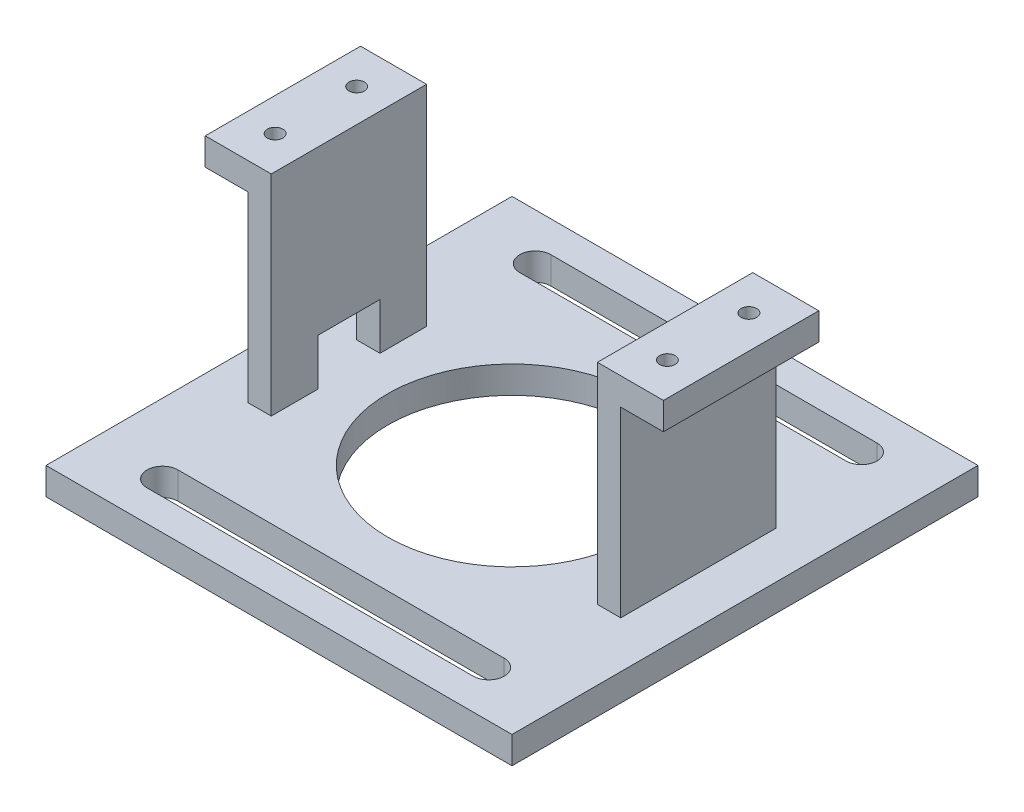
SolidWorks part; units mm, degrees
ref_plane "Alzado" through (0, 0, 0) normal (0, 0, 1) x (1, 0, 0)
ref_plane "Planta" through (0, 0, 0) normal (0, 1, 0) x (1, 0, 0)
ref_plane "Vista lateral" through (0, 0, 0) normal (1, 0, 0) x (0, 0, -1)
sketch "Croquis1" plane through (0, 0, 0) normal (0, 1, 0) x (1, 0, 0)
  line L0 (-49.5899, 38.6898) -> (-49.5899, -21.3102)
  line L1 (-49.5899, 38.6898) -> (10.4101, 38.6898)
  line L2 (10.4101, 38.6898) -> (10.4101, -21.3102)
  line L3 (10.4101, -21.3102) -> (-49.5899, -21.3102)
extrude "Saliente-Extruir1" add sketch "Croquis1" along normal blind 3.5 contours L3 L0 L1 L2
sketch "Croquis2" plane through (0, 3.5, 0) normal (0, 1, 0) x (1, 0, 0)
  line L9 (1.4101, -1.3102) -> (4.4101, -1.3102)
  line L10 (4.4101, -1.3102) -> (4.4101, 18.6898)
  line L11 (4.4101, 18.6898) -> (1.4101, 18.6898)
  line L12 (1.4101, 18.6898) -> (1.4101, -1.3102)
  line L13 (-40.5899, -1.3102) -> (-43.5899, -1.3102)
  line L14 (-43.5899, -1.3102) -> (-43.5899, 18.6898)
  line L15 (-43.5899, 18.6898) -> (-40.5899, 18.6898)
  line L16 (-40.5899, 18.6898) -> (-40.5899, -1.3102)
extrude "Saliente-Extruir4" add sketch "Croquis2" along normal blind 27
sketch "Croquis7" plane through (0, 3.5, 0) normal (0, 1, 0) x (1, 0, 0)
  circle A0 centre (-19.5899, 8.6898) radius 16
extrude "Cortar-Extruir2" cut sketch "Croquis7" against normal blind 5 contours A0
sketch "Croquis8" plane through (0, 3.5, 0) normal (0, 1, 0) x (1, 0, 0)
  line L2 (1.4101, -17.3102) -> (-40.5899, -17.3102)
  line L4 (-40.5899, -13.3102) -> (1.4101, -13.3102)
  line L6 (1.4101, 30.6898) -> (-40.5899, 30.6898)
  line L8 (1.4101, 34.6898) -> (-40.5899, 34.6898)
  arc A1 (-40.5899, 34.6898) -> (-40.5899, 30.6898) centre (-40.5899, 32.6898) ccw
  arc A2 (-40.5899, -13.3102) -> (-40.5899, -17.3102) centre (-40.5899, -15.3102) ccw
  arc A3 (1.4101, -17.3102) -> (1.4101, -13.3102) centre (1.4101, -15.3102) ccw
  arc A4 (1.4101, 30.6898) -> (1.4101, 34.6898) centre (1.4101, 32.6898) ccw
extrude "Cortar-Extruir3" cut sketch "Croquis8" against normal blind 5
sketch "Croquis9" plane through (4.4101, 0, 0) normal (1, 0, 0) x (0, 0, -1)
  line L0 (-1.3102, 30.5) -> (18.6898, 30.5)
  line L1 (18.6898, 30.5) -> (18.6898, 27)
  line L2 (18.6898, 30.5) -> (18.6898, 3.5) construction
  line L3 (18.6898, 27) -> (-1.3102, 27)
  line L4 (-1.3102, 30.5) -> (-1.3102, 3.5) construction
  line L5 (-1.3102, 27) -> (-1.3102, 30.5)
extrude "Saliente-Extruir5" add sketch "Croquis9" along normal blind 5.5
sketch "Croquis10" plane through (-43.5899, 0, 0) normal (-1, 0, 0) x (0, 0, 1)
  line L0 (1.3102, 30.5) -> (-18.6898, 30.5)
  line L1 (-18.6898, 30.5) -> (-18.6898, 3.5) construction
  line L2 (-18.6898, 30.5) -> (1.3102, 30.5) construction
  line L3 (-18.6898, 30.5) -> (-18.6898, 27)
  line L4 (-18.6898, 27) -> (1.3102, 27)
  line L5 (1.3102, 30.5) -> (1.3102, 3.5) construction
  line L6 (1.3102, 27) -> (1.3102, 30.5)
extrude "Saliente-Extruir6" add sketch "Croquis10" along normal blind 5.5 contours L4 L6 L0 L3
sketch "Croquis11" plane through (0, 30.5, 0) normal (0, 1, 0) x (1, 0, 0)
  circle A0 centre (-44.8399, 3.4398) radius 1
  circle A1 centre (-44.8399, 13.9398) radius 1
extrude "Cortar-Extruir4" cut sketch "Croquis11" against normal blind 5.5 contours A1 | A0
sketch "Croquis13" plane through (0, 30.5, 0) normal (0, 1, 0) x (1, 0, 0)
  circle A0 centre (5.6601, 3.4398) radius 1
  circle A1 centre (5.6601, 13.9398) radius 1
extrude "Cortar-Extruir5" cut sketch "Croquis13" against normal blind 5.5
sketch "Croquis14" plane through (-43.5899, 0, 0) normal (-1, 0, 0) x (0, 0, 1)
  line L0 (-4.6898, 9.5) -> (-12.6898, 9.5)
  line L8 (-12.6898, 9.5) -> (-12.6898, 3.5)
  line L9 (-12.6898, 3.5) -> (-4.6898, 3.5)
  line L10 (-4.6898, 3.5) -> (-4.6898, 9.5)
extrude "Cortar-Extruir6" cut sketch "Croquis14" against normal blind 10
